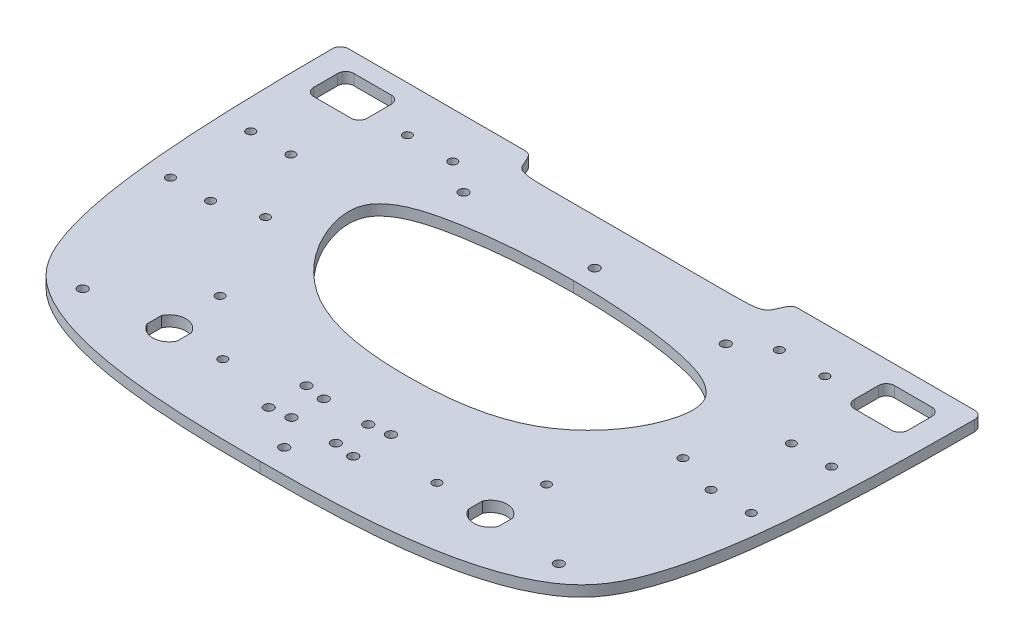
SolidWorks part; units mm, degrees
ref_plane "Front Plane" through (0, 0, 0) normal (0, 0, 1) x (1, 0, 0)
ref_plane "Top Plane" through (0, 0, 0) normal (0, 1, 0) x (1, 0, 0)
ref_plane "Right Plane" through (0, 0, 0) normal (1, 0, 0) x (0, 0, -1)
sketch "Sketch1" plane through (0, 0, 0) normal (0, 1, 0) x (1, 0, 0)
  line L1 (-120, 155) -> (120, 155)
  line L2 (-120, 155) -> (-120, -155)
  line L3 (-120, -155) -> (120, -155)
  line L4 (120, 155) -> (120, -155)
  point P4 (0, 155)
  point P6 (-120, 0)
  dimension "D1" = 240
  dimension "D2" = 310
extrude "Boss-Extrude1" add sketch "Sketch1" along normal blind 4 contours L2 L1 L4 L3
sketch "Sketch2" plane through (0, 4, 0) normal (0, 1, 0) x (1, 0, 0)
  line L0 (-120, 155) -> (120, 155) construction
  line L1 (-120, 0) -> (120, 0)
  line L2 (-120, 155) -> (-120, -155) construction
  circle B0 centre (49, -30) radius 1.75
  circle B1 centre (-49, -30) radius 1.75
  circle B2 centre (-88.957, -132.3382) radius 1.75
  circle B3 centre (0, -146) radius 1.75
  circle B4 centre (88.957, -132.3382) radius 1.75
  circle B5 centre (110.4185, 44.9345) radius 1.75
  circle B6 centre (88.957, 132.3382) radius 1.75
  circle B7 centre (0, 146) radius 1.75
  circle B8 centre (-88.957, 132.3382) radius 1.75
  circle B9 centre (-110.4185, 44.9345) radius 1.75
  spline B10 degree 3 poles (0, 155) (30.5722, 155) (80.3433, 153.7333) (119.2212, 117.6544) (120, 45.41) (120, 0) knots 0 0 0 0 0.458017 0.558017 1 1 1 1
  spline B11 degree 3 poles (0, 155) (-30.5722, 155) (-80.3433, 153.7333) (-119.2212, 117.6544) (-120, 45.41) (-120, 0) knots 0 0 0 0 0.458017 0.558017 1 1 1 1
  spline B12 degree 3 poles (0, -155) (30.5722, -155) (80.3433, -153.7333) (119.2212, -117.6544) (120, -45.41) (120, 0) knots 0 0 0 0 0.458017 0.558017 1 1 1 1
  spline B13 degree 3 poles (0, -155) (-30.5722, -155) (-80.3433, -153.7333) (-119.2212, -117.6544) (-120, -45.41) (-120, 0) knots 0 0 0 0 0.458017 0.558017 1 1 1 1
  line M2 (-120, -155) -> (120, -155)
  line M3 (120, -155) -> (120, 155)
  line M4 (120, 155) -> (-120, 155)
  line M5 (-120, 155) -> (-120, -155)
sketch_block_instance "Base-2-F1-1"
sketch_block "Base-2-F1"
extrude "Cut-Extrude1" cut sketch "Sketch2" against normal up to next contours B11 M4 M5 | B10 M4 M3 | B12 M2 M3 | B13 M2 M5 | B8 | B7 | B6 | B9 | B1 | B0 | B2 | B3 | B4 | B5
sketch "Sketch3" plane through (0, 4, 0) normal (0, 1, 0) x (1, 0, 0)
  line L5 (-120, 0) -> (120, 0)
  line L6 (-120, 0) -> (-120, 155)
  line L7 (-120, 155) -> (120, 155)
  line L8 (120, 0) -> (120, 155)
  line L9 (-120, 0) -> (120, 0)
  line L10 (-120, 0) -> (-120, -5)
  line L11 (-120, -5) -> (120, -5)
  line L12 (120, 0) -> (120, -5)
  circle M5 centre (110.4185, 44.9345) radius 1.75
  circle M8 centre (88.957, 132.3382) radius 1.75
  circle M9 centre (0, 146) radius 1.75
  circle M10 centre (-110.4185, 44.9345) radius 1.75
  circle M14 centre (-88.957, 132.3382) radius 1.75
  spline M15 degree 3 poles (0, 155) (-30.5722, 155) (-80.3433, 153.7333) (-119.2212, 117.6544) (-120, 45.41) (-120, 0) knots 0 0 0 0 0.458017 0.558017 1 1 1 1
  spline M16 degree 3 poles (-120, 0) (-120, -45.41) (-119.2212, -117.6544) (-80.3433, -153.7333) (-30.5722, -155) (0, -155) knots 0 0 0 0 0.441983 0.541983 1 1 1 1
  spline M17 degree 3 poles (0, -155) (30.5722, -155) (80.3433, -153.7333) (119.2212, -117.6544) (120, -45.41) (120, 0) knots 0 0 0 0 0.458017 0.558017 1 1 1 1
  spline M18 degree 3 poles (120, 0) (120, 45.41) (119.2212, 117.6544) (80.3433, 153.7333) (30.5722, 155) (0, 155) knots 0 0 0 0 0.441983 0.541983 1 1 1 1
  dimension "D1" = 240
  dimension "D2" = 155
  dimension "D3" = 5
extrude "Cut-Extrude2" cut sketch "Sketch3" against normal through all contours L11 L5 M16 M17 | L5 M15 M18 M5 M9 M14 M10 M8
sketch "Sketch4" plane through (0, 4, 0) normal (0, 1, 0) x (1, 0, 0)
  line L0 (49, -30) -> (-49, -30) construction
  circle A0 centre (0, -30) radius 1.75
  dimension "D1" = 3.5
extrude "Cut-Extrude3" cut sketch "Sketch4" against normal through all
sketch "Sketch5" plane through (0, 4, 0) normal (0, 1, 0) x (1, 0, 0)
  line L1 (-119.9969, -5) -> (119.9969, -5) construction
  line L2 (0, -5) -> (0, -13) construction
  line L3 (-51, -5) -> (51, -5)
  line L4 (-51, -5) -> (-51, -13) construction
  line L5 (-51, -13) -> (51, -13) construction
  line L6 (51, -5) -> (51, -13) construction
  line L7 (-34.5426, -13) -> (34.5426, -13)
  spline S0 degree 3 poles (-51, -5) (-49.1296, -5) (-47.569, -8.0005) (-47.3764, -8.7754) (-45.5407, -12.6537) (-41.6826, -13) (-34.5426, -13) knots 0 0 0 0 0.228374 0.4873 0.564462 1 1 1 1
  spline S1 degree 3 poles (51, -5) (49.1296, -5) (47.569, -8.0005) (47.3764, -8.7754) (45.5407, -12.6537) (41.6826, -13) (34.5426, -13) knots 0 0 0 0 0.228374 0.4873 0.564462 1 1 1 1
  point P0 (0, -18)
  point P17 (0, -5)
  line B0 (-61, -109) -> (-61, -22) construction
  line B1 (65, -113) -> (65, -18) construction
  line B2 (-65, -18) -> (65, -18) construction
  circle B3 centre (-61, -109) radius 1.6
  circle B4 centre (-61, -22) radius 1.6
  circle B5 centre (61, -22) radius 1.6
  circle B6 centre (61, -109) radius 1.6
  dimension "D3" = 13
  dimension "D4" = 8
sketch_block_instance "MCU-BOARD-1"
sketch_block "MCU-BOARD" parameters "D3"=3.2, "D1"=87, "D2"=122
extrude "Cut-Extrude4" cut sketch "Sketch5" against normal through all
sketch "Sketch6" plane through (0, 4, 0) normal (0, 1, 0) x (1, 0, 0)
  line L0 (0, 0) -> (0, -155) construction
  line L2 (-34.5426, -13) -> (34.5426, -13) construction
  spline S0 degree 3 poles (0, -38) (-12.4508, -38) (-30.6891, -38.9696) (-50.2216, -43.37) (-57.8657, -46.3056) (-66.3186, -54.2579) (-62.7732, -68.0265) (-54.3731, -81.4806) (-35.7525, -98.0785) (-12.6383, -100) (0, -100) knots 0 0 0 0 0.264131 0.321741 0.388217 0.419342 0.536424 0.607787 0.734445 1 1 1 1
  spline S1 degree 3 poles (0, -38) (12.4508, -38) (30.6891, -38.9696) (50.2216, -43.37) (57.8657, -46.3056) (66.3186, -54.2579) (62.7732, -68.0265) (54.3731, -81.4806) (35.7525, -98.0785) (12.6383, -100) (0, -100) knots 0 0 0 0 0.264131 0.321741 0.388217 0.419342 0.536424 0.607787 0.734445 1 1 1 1
  dimension "D1" = 62
  dimension "D2" = 25
extrude "Cut-Extrude5" cut sketch "Sketch6" against normal through all
sketch "Sketch8" plane through (0, 4, 0) normal (0, 1, 0) x (1, 0, 0)
  line L0 (0, 0) -> (0, -155) construction
  line L1 (-15.8, -128.95) -> (15.8, -128.95) construction
  circle A0 centre (-8.3, -122.9) radius 1.75
  circle A1 centre (8.3, -122.9) radius 1.75
  circle A2 centre (8.3, -135) radius 1.75
  circle A3 centre (-8.3, -135) radius 1.75
  point P6 (0, -118.9)
  line B0 (11.05, -120.15) -> (11.05, -137.75) construction
  line B1 (-15.8, -118.9) -> (15.8, -118.9) construction
  line B2 (-15.8, -139) -> (15.8, -139) construction
  line B3 (-15.8, -124.9) -> (-15.8, -133) construction
  circle B4 centre (-15.8, -121.9) radius 1.75
  circle B5 centre (-15.8, -136) radius 1.75
  circle B6 centre (15.8, -136) radius 1.75
  circle B7 centre (15.8, -121.9) radius 1.75
  dimension "D1" = 16
sketch_block_instance "GY87-Holder-1"
sketch_block "GY87-Holder"
extrude "Cut-Extrude7" cut sketch "Sketch8" against normal through all
fillet "Fillet1" radius 3 2 edges at (119.9969, 2, 5) (-119.9969, 2, 5)
sketch "Sketch13" plane through (0, 4, 0) normal (0, 1, 0) x (1, 0, 0)
  line L1 (94, -12) -> (108, -12)
  line L5 (91, -15) -> (91, -24)
  line L6 (94, -27) -> (108, -27)
  line L7 (111, -15) -> (111, -24)
  line L8 (51, -5) -> (116.9911, -5) construction
  line L9 (0, 0) -> (0, -155) construction
  line L10 (-94, -27) -> (-108, -27)
  line L11 (-111, -15) -> (-111, -24)
  line L12 (-94, -12) -> (-108, -12)
  line L13 (-91, -15) -> (-91, -24)
  arc A3 (108, -27) -> (111, -24) centre (108, -24) ccw
  arc A4 (108, -12) -> (111, -15) centre (108, -15) cw
  arc A5 (91, -24) -> (94, -27) centre (94, -24) ccw
  arc A6 (94, -12) -> (91, -15) centre (94, -15) ccw
  arc A7 (-108, -27) -> (-111, -24) centre (-108, -24) cw
  arc A8 (-108, -12) -> (-111, -15) centre (-108, -15) ccw
  arc A9 (-91, -24) -> (-94, -27) centre (-94, -24) cw
  arc A10 (-94, -12) -> (-91, -15) centre (-94, -15) cw
  point P11 (61, -22)
  point P18 (111, -12)
  point P21 (91, -27)
  point P24 (91, -12)
  dimension "D1" = 15
  dimension "D2" = 20
  dimension "D4" = 3
  dimension "D3" = 7
  dimension "D5" = 30
extrude "Cut-Extrude9" cut sketch "Sketch13" against normal through all
sketch "Sketch14" plane through (0, 4, 0) normal (0, 1, 0) x (1, 0, 0)
  line L0 (0, 0) -> (0, -155) construction
  circle A0 centre (78, -75) radius 1.6
  circle A1 centre (78, -22) radius 1.6
  circle A2 centre (40, -128.95) radius 1.6
  circle A3 centre (-40, -128.95) radius 1.6
  circle A4 centre (-78, -75) radius 1.6
  circle A5 centre (-78, -22) radius 1.6
  point P3 (0, -155)
  dimension "D1" = 3.2
  dimension "D2" = 80
  dimension "D3" = 78
  dimension "D4" = 26.05
  dimension "D5" = 40
  dimension "D6" = 53
extrude "Cut-Extrude10" cut sketch "Sketch14" against normal through all
sketch "Sketch15" plane through (0, 4, 0) normal (0, 1, 0) x (1, 0, 0)
  line L0 (94, -27) -> (108, -27) construction
  line L6 (0, 0) -> (0, -155) construction
  line L43 (51, -5) -> (116.9911, -5) construction
  line L44 (93.5, -50) -> (108.5, -50) construction
  line L65 (93.5, -50) -> (93.5, -80) construction
  line L66 (93.5, -80) -> (108.5, -80) construction
  line L67 (108.5, -50) -> (108.5, -80) construction
  circle A0 centre (93.5, -50) radius 1.6
  circle A1 centre (93.5, -80) radius 1.6
  circle A2 centre (108.5, -50) radius 1.6
  circle A3 centre (108.5, -80) radius 1.6
  circle A4 centre (-108.5, -50) radius 1.6
  circle A5 centre (-108.5, -80) radius 1.6
  circle A6 centre (-93.5, -80) radius 1.6
  circle A7 centre (-93.5, -50) radius 1.6
  point P6 (101, -27)
  point P7 (101, -50)
  point P8 (108.5, -65)
  dimension "D4" = 3.2
  dimension "D1" = 15
  dimension "D2" = 30
  dimension "D3" = 60
extrude "Cut-Extrude11" cut sketch "Sketch15" against normal through all
sketch "Sketch16" plane through (0, 4, 0) normal (0, 1, 0) x (1, 0, 0)
  line L0 (-40, -128.95) -> (40, -128.95) construction
  line L1 (0, 0) -> (0, -155) construction
  line L2 (54.4, -126.2892) -> (54.4, -131.6108)
  line L3 (65.6, -126.2892) -> (65.6, -131.6108)
  line L4 (-65.6, -126.2892) -> (-65.6, -131.6108)
  line L5 (-54.4, -126.2892) -> (-54.4, -131.6108)
  arc A0 (54.4, -131.6108) -> (65.6, -131.6108) centre (60, -128.95) ccw
  arc A1 (65.6, -126.2892) -> (54.4, -126.2892) centre (60, -128.95) ccw
  arc A2 (-65.6, -126.2892) -> (-54.4, -126.2892) centre (-60, -128.95) cw
  arc A3 (-54.4, -131.6108) -> (-65.6, -131.6108) centre (-60, -128.95) cw
  dimension "D1" = 12.4
  dimension "D2" = 60
  dimension "D3" = 11.2
extrude "Cut-Extrude12" cut sketch "Sketch16" against normal through all
